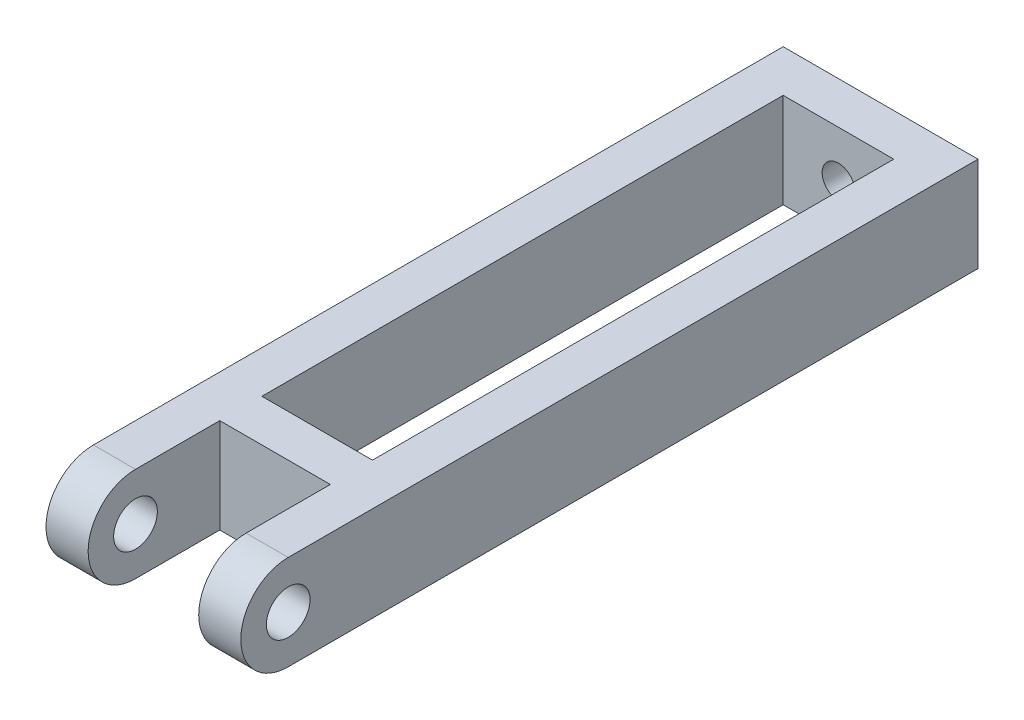
SolidWorks part; units mm, degrees
ref_plane "Front Plane" through (0, 0, 0) normal (0, 0, 1) x (1, 0, 0)
ref_plane "Top Plane" through (0, 0, 0) normal (0, 1, 0) x (1, 0, 0)
ref_plane "Right Plane" through (0, 0, 0) normal (1, 0, 0) x (0, 0, -1)
sketch "Sketch1" plane through (0, 0, 0) normal (1, 0, 0) x (0, 0, -1)
  line L0 (0, 4.5) -> (65.5, 4.5)
  line L5 (0, -4.5) -> (65.5, -4.5)
  line L6 (65.5, 4.5) -> (65.5, -4.5)
  circle A1 centre (0, 0) radius 2.075
  arc A2 (0, 4.5) -> (0, -4.5) centre (0, 0) ccw
  dimension "D2" = 4.5
  dimension "D1" = 4.15
  dimension "D3" = 65.5
extrude "Boss-Extrude1" add sketch "Sketch1" against normal blind 4
sketch "Sketch2" plane through (0, 0, 0) normal (1, 0, 0) x (0, 0, -1)
  line L0 (65.5, 4.5) -> (0, 4.5) construction
  line L1 (8, 4.5) -> (65.5, 4.5)
  line L2 (8, 4.5) -> (8, -4.5)
  line L3 (8, -4.5) -> (65.5, -4.5)
  line L4 (65.5, 4.5) -> (65.5, -4.5)
  line L5 (0, -4.5) -> (65.5, -4.5) construction
  line L11 (65.5, -4.5) -> (65.5, 4.5) construction
  dimension "D1" = 8
extrude "Boss-Extrude2" add sketch "Sketch2" along normal blind 5.25
mirror "Mirror2" about plane through (5.25, 0, 0) normal (1, 0, 0) of bodies 103
sketch "Sketch3" plane through (0, 0, 0) normal (0, 1, 0) x (1, 0, 0)
  line L0 (0, 8) -> (0, 0) construction
  line L1 (0, 12) -> (10.5, 12)
  line L2 (0, 12) -> (0, 61.5)
  line L3 (0, 61.5) -> (10.5, 61.5)
  line L4 (10.5, 12) -> (10.5, 61.5)
  line L5 (10.5, 8) -> (10.5, 0) construction
  line L7 (10.5, 8) -> (0, 8) construction
  line L8 (-4, 65.5) -> (14.5, 65.5) construction
  dimension "D1" = 4
  dimension "D2" = 4
extrude "Cut-Extrude1" cut sketch "Sketch3" against normal blind 11 and the other way blind 11
ref_plane "Plane1" through (0, 0, -60) normal (0, 0, 1) x (1, 0, 0)
sketch "Sketch4" plane through (0, 0, -60) normal (0, 0, 1) x (1, 0, 0)
  circle A0 centre (5.25, 0) radius 1.55
  point P2 (0, 0)
  point P4 (0, 0)
  dimension "D1" = 3.1
  dimension "D2" = 5.25
extrude "Cut-Extrude2" cut sketch "Sketch4" against normal blind 11
